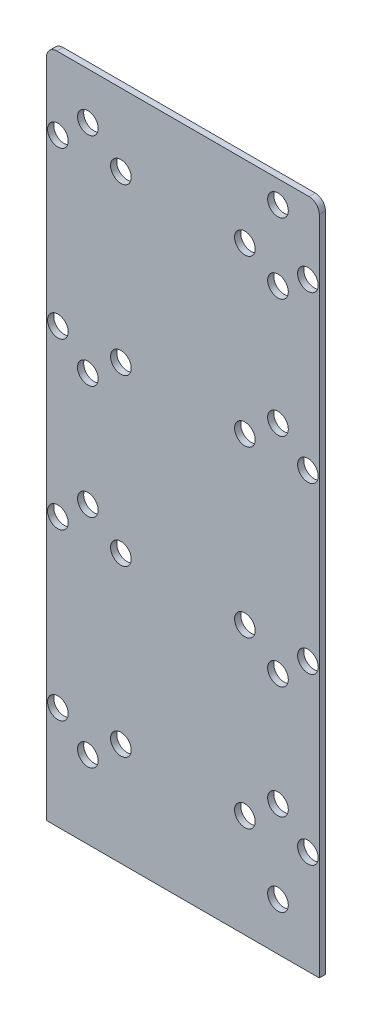
SolidWorks part; units mm, degrees
ref_plane "Front Plane" through (0, 0, 0) normal (0, 0, 1) x (1, 0, 0)
ref_plane "Top Plane" through (0, 0, 0) normal (0, 1, 0) x (1, 0, 0)
ref_plane "Right Plane" through (0, 0, 0) normal (1, 0, 0) x (0, 0, -1)
ref_plane "Plane4" through (0, 0, 3) normal (0, 0, 1) x (1, 0, 0)
sketch "Sketch1" plane through (0, 0, 3) normal (0, 0, 1) x (1, 0, 0)
  line L6 (-41.1488, 528.3974) -> (90.8512, 528.3974)
  line L7 (-41.1488, 528.3974) -> (-41.1488, 203.3974)
  line L8 (-41.1488, 203.3974) -> (90.8512, 203.3974)
  line L9 (90.8512, 528.3974) -> (90.8512, 203.3974)
  dimension "D1" = 325
  dimension "D2" = 132
extrude "Boss-Extrude1" add sketch "Sketch1" against normal blind 3
sketch "Sketch2" plane through (0, 0, 3) normal (0, 0, 1) x (1, 0, 0)
  line L0 (90.8512, 528.3974) -> (-41.1488, 528.3974) construction
  line L1 (90.8512, 203.3974) -> (90.8512, 528.3974) construction
  line L2 (-41.1488, 203.3974) -> (90.8512, 203.3974) construction
  circle A0 centre (70.8512, 517.3974) radius 5
  circle A1 centre (70.8512, 483.3974) radius 5
  circle A2 centre (70.8512, 425.8974) radius 5
  circle A3 centre (70.8512, 320.8974) radius 5
  circle A4 centre (70.8512, 266.3974) radius 5
  circle A5 centre (70.8512, 226.3974) radius 5
  dimension "D1" = 10
  dimension "D2" = 11
  dimension "D3" = 20
  dimension "D4" = 23
  dimension "D5" = 63
  dimension "D6" = 117.5
  dimension "D7" = 222.5
  dimension "D8" = 280
extrude "Cut-Extrude1" cut sketch "Sketch2" against normal through all
sketch "Sketch3" plane through (0, 0, 3) normal (0, 0, 1) x (1, 0, 0)
  line L0 (-41.1488, 203.3974) -> (90.8512, 203.3974) construction
  line L1 (-21.1488, 505.8974) -> (-21.1488, 400.8974) construction
  line L2 (-21.1488, 400.8974) -> (-21.1488, 345.8974) construction
  line L3 (-21.1488, 345.8974) -> (-21.1488, 240.8974) construction
  line L4 (-41.1488, 528.3974) -> (-41.1488, 203.3974) construction
  circle A0 centre (-21.1488, 505.8974) radius 5
  circle A1 centre (-21.1488, 400.8974) radius 5
  circle A2 centre (-21.1488, 345.8974) radius 5
  circle A3 centre (-21.1488, 240.8974) radius 5
  dimension "D5" = 10
  dimension "D1" = 37.5
  dimension "D2" = 142.5
  dimension "D3" = 197.5
  dimension "D4" = 302.5
  dimension "D6" = 20
extrude "Cut-Extrude2" cut sketch "Sketch3" against normal blind 10
sketch "Sketch4" plane through (0, 0, 3) normal (0, 0, 1) x (1, 0, 0)
  line L0 (85.3512, 253.3974) -> (54.8512, 253.3974) construction
  line L1 (54.8512, 253.3974) -> (-5.1488, 253.3974) construction
  line L2 (-5.1488, 253.3974) -> (-35.6488, 253.3974) construction
  line L3 (-41.1488, 203.3974) -> (90.8512, 203.3974) construction
  circle A0 centre (-35.6488, 253.3974) radius 5
  circle A1 centre (-5.1488, 253.3974) radius 5
  circle A2 centre (54.8512, 253.3974) radius 5
  circle A3 centre (85.3512, 253.3974) radius 5
  point P10 (24.8512, 253.3974)
  point P11 (24.8512, 203.3974)
  dimension "D1" = 10
  dimension "D2" = 30.5
  dimension "D3" = 30.5
  dimension "D4" = 60
  dimension "D5" = 50
extrude "Cut-Extrude3" cut sketch "Sketch4" against normal blind 10
pattern_linear "LPattern1" count 4 spacing 80 along (0, 1, 0) of "Cut-Extrude3"
fillet "Fillet1" radius 5 2 edges at (90.8512, 528.3974, 1.5) (-41.1488, 528.3974, 1.5)
